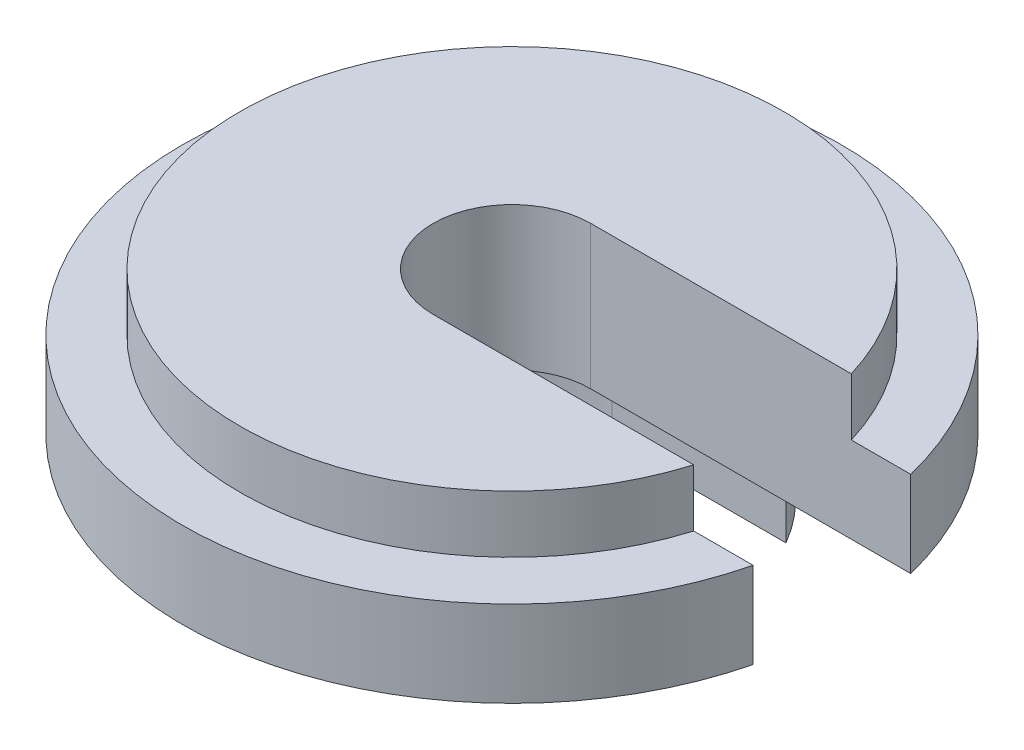
SolidWorks part; units mm, degrees
ref_plane "Front Plane" through (0, 0, 0) normal (0, 0, 1) x (1, 0, 0)
ref_plane "Top Plane" through (0, 0, 0) normal (0, 1, 0) x (1, 0, 0)
ref_plane "Right Plane" through (0, 0, 0) normal (1, 0, 0) x (0, 0, -1)
sketch "Sketch1" plane through (0, 0, 0) normal (0, 0, 1) x (1, 0, 0)
  line L0 (0, 0) -> (7, 0)
  line L1 (7, 0) -> (7, 2)
  line L2 (7, 2) -> (11.5, 2)
  line L3 (11.5, 2) -> (11.5, 5)
  line L4 (11.5, 5) -> (9.5, 5)
  line L5 (9.5, 5) -> (9.5, 7)
  line L6 (9.5, 7) -> (0, 7)
  line L7 (0, 7) -> (0, 0)
  dimension "D1" = 7
  dimension "D2" = 9.5
  dimension "D3" = 11.5
  dimension "D4" = 2
  dimension "D5" = 3
  dimension "D6" = 2
revolve "Revolve1" add sketch "Sketch1" angle 360 about L7
sketch "Sketch3" plane through (0, 0, 0) normal (0, -1, 0) x (1, 0, 0)
  line L0 (0, 3.5) -> (6.0622, 3.5)
  line L1 (0, -3.5) -> (6.0622, -3.5)
  arc A0 (0, 3.5) -> (0, -3.5) centre (0, 0) ccw
  circle A1 centre (0, 0) radius 7 construction
  arc A2 (6.0622, -3.5) -> (6.0622, 3.5) centre (0, 0) ccw
  dimension "D1" = 7
extrude "Cut-Extrude1" cut sketch "Sketch3" against normal blind 2
sketch "Sketch4" plane through (0, 7, 0) normal (0, 1, 0) x (1, 0, 0)
  line L0 (0, 2.75) -> (11.1664, 2.75)
  line L1 (0, -2.75) -> (11.1664, -2.75)
  arc A0 (0, 2.75) -> (0, -2.75) centre (0, 0) ccw
  circle A1 centre (0, 0) radius 11.5 construction
  arc A2 (11.1664, -2.75) -> (11.1664, 2.75) centre (0, 0) ccw
  dimension "D1" = 5.5
extrude "Cut-Extrude2" cut sketch "Sketch4" against normal blind 11
